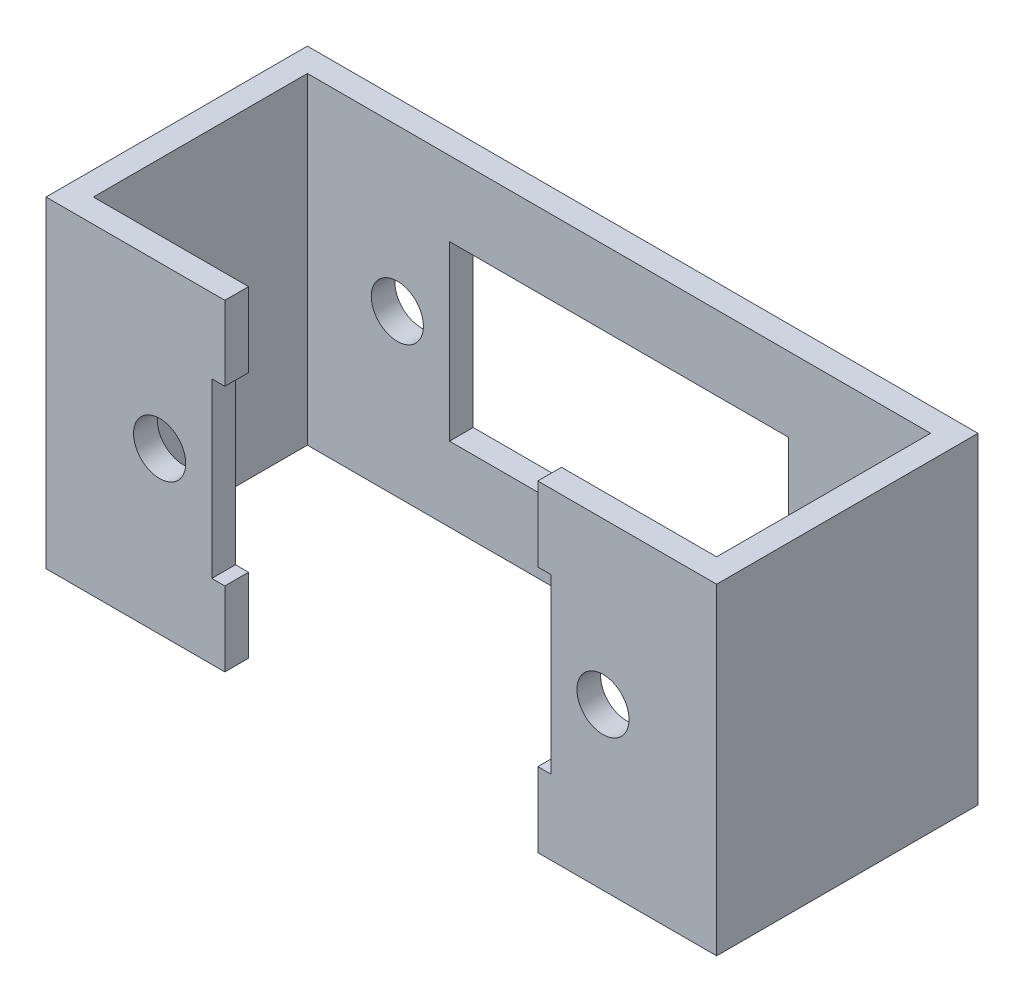
SolidWorks part; units mm, degrees
material "6061 Alloy"
ref_plane "Front Plane" through (0, 0, 0) normal (0, 0, 1) x (1, 0, 0)
ref_plane "Top Plane" through (0, 0, 0) normal (0, 1, 0) x (1, 0, 0)
ref_plane "Right Plane" through (0, 0, 0) normal (1, 0, 0) x (0, 0, -1)
sketch "Sketch2" plane through (0, 0, 0) normal (0, 1, 0) x (1, 0, 0)
  line L0 (-22.5, 0) -> (22.5, 0)
  line L1 (22.5, 0) -> (22.5, -17.54)
  line L2 (22.5, -17.54) -> (10.5, -17.54)
  line L3 (10.5, -17.54) -> (10.5, -15.95)
  line L4 (10.5, -15.95) -> (20.91, -15.95)
  line L5 (20.91, -15.95) -> (20.91, -1.59)
  line L6 (20.91, -1.59) -> (-20.91, -1.59)
  line L7 (-20.91, -1.59) -> (-20.91, -15.95)
  line L8 (-20.91, -15.95) -> (-10.5, -15.95)
  line L9 (-10.5, -15.95) -> (-10.5, -17.54)
  line L10 (-10.5, -17.54) -> (-22.5, -17.54)
  line L11 (-22.5, -17.54) -> (-22.5, 0)
  point P16 (22.5, -8.77)
  point P17 (-16.5, -17.54)
  point P18 (0, 0)
  dimension "D1" = 45
  dimension "D2" = 1.59
  dimension "D3" = 1.59
  dimension "D4" = 1.59
  dimension "D5" = 1.59
  dimension "D6" = 17.54
  dimension "D7" = 12
  dimension "D8" = 12
extrude "Boss-Extrude1" add sketch "Sketch2" along normal blind 21.6
sketch "Sketch3" plane through (0, 0, 17.54) normal (0, 0, 1) x (1, 0, 0)
  line L0 (-22.5, 10.8) -> (22.5, 10.8) construction
  line L1 (-22.5, 21.6) -> (-22.5, 0) construction
  line L2 (22.5, 21.6) -> (22.5, 0) construction
  circle A0 centre (-15, 10.8) radius 1.25
  circle A1 centre (15, 10.8) radius 1.25
  dimension "D1" = 30
  dimension "D3" = 2.5
  dimension "D2" = 15
extrude "Cut-Extrude1" [suppressed] cut sketch "Sketch3" against normal blind 2
sketch "Sketch4" plane through (0, 0, 0) normal (0, 0, -1) x (-1, 0, 0)
  line L0 (-22.5, 10.8) -> (22.5, 10.8) construction
  line L1 (-22.5, 21.6) -> (-22.5, 0) construction
  line L2 (22.5, 21.6) -> (22.5, 0) construction
  line L4 (-11.375, 16.6) -> (11.375, 16.6)
  line L5 (-11.375, 16.6) -> (-11.375, 5)
  line L6 (-11.375, 5) -> (11.375, 5)
  line L7 (11.375, 16.6) -> (11.375, 5)
  line L8 (-11.375, 16.6) -> (11.375, 5) construction
  line L9 (-11.375, 5) -> (11.375, 16.6) construction
  circle A0 centre (-14.875, 10.8) radius 1.75
  circle A1 centre (14.875, 10.8) radius 1.75
  point P6 (0, 10.8)
  dimension "D5" = 3.5
  dimension "D1" = 22.75
  dimension "D2" = 11.6
  dimension "D3" = 3.5
  dimension "D4" = 3.5
extrude "Cut-Extrude2" cut sketch "Sketch4" against normal blind 20
